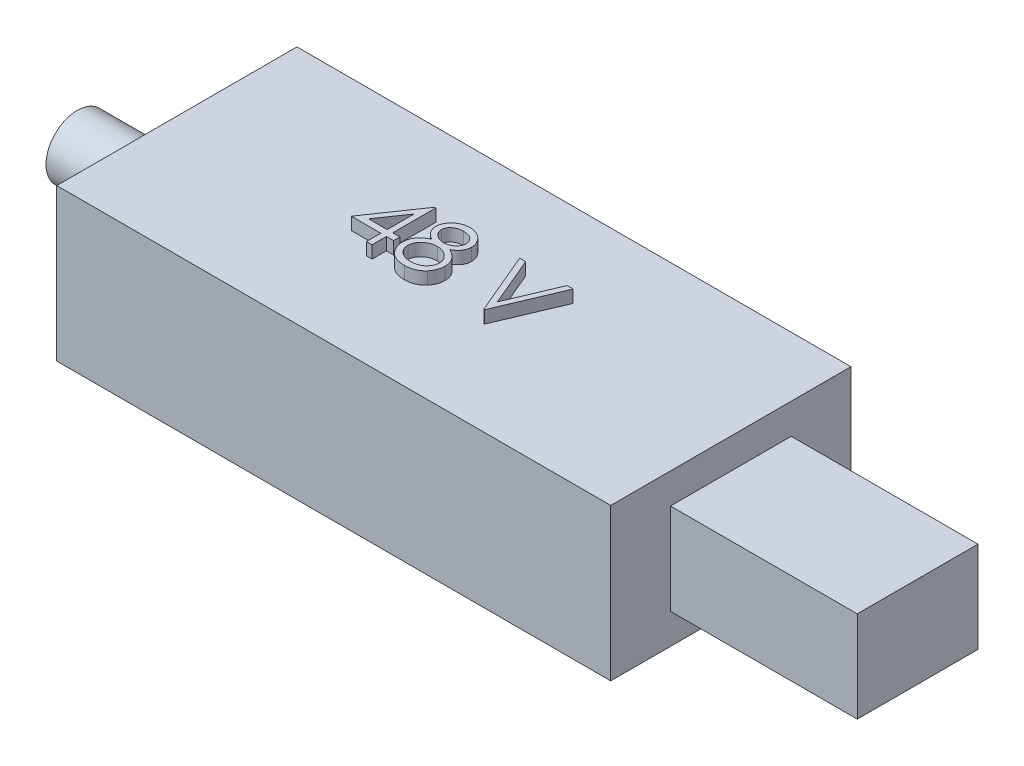
SolidWorks part; units mm, degrees
ref_plane "Front Plane" through (0, 0, 0) normal (0, 0, 1) x (1, 0, 0)
ref_plane "Top Plane" through (0, 0, 0) normal (0, 1, 0) x (1, 0, 0)
ref_plane "Right Plane" through (0, 0, 0) normal (1, 0, 0) x (0, 0, -1)
sketch "Sketch1" plane through (0, 0, 0) normal (0, 1, 0) x (1, 0, 0)
  line L1 (-56.5, 24.5) -> (56.5, 24.5)
  line L2 (-56.5, 24.5) -> (-56.5, -24.5)
  line L3 (-56.5, -24.5) -> (56.5, -24.5)
  line L4 (56.5, 24.5) -> (56.5, -24.5)
  line L5 (-56.5, 24.5) -> (56.5, -24.5) construction
  line L6 (-56.5, -24.5) -> (56.5, 24.5) construction
  point P0 (0, 0)
  dimension "D1" = 113
  dimension "D2" = 49
extrude "Boss-Extrude1" add sketch "Sketch1" along normal blind 31
sketch "Sketch2" plane through (56.5, 0, 0) normal (1, 0, 0) x (0, 0, -1)
  line L0 (-24.5, 15.5) -> (24.5, 15.5) construction
  line L1 (-24.5, 31) -> (-24.5, 0) construction
  line L2 (24.5, 31) -> (24.5, 0) construction
  line L4 (-12.3134, 24.7992) -> (12.3134, 24.7992)
  line L5 (-12.3134, 24.7992) -> (-12.3134, 6.2008)
  line L6 (-12.3134, 6.2008) -> (12.3134, 6.2008)
  line L7 (12.3134, 24.7992) -> (12.3134, 6.2008)
  line L8 (-12.3134, 24.7992) -> (12.3134, 6.2008) construction
  line L9 (-12.3134, 6.2008) -> (12.3134, 24.7992) construction
  point P6 (0, 15.5)
extrude "Boss-Extrude2" add sketch "Sketch2" along normal blind 38.1
sketch "Sketch3" plane through (-56.5, 0, 0) normal (-1, 0, 0) x (0, 0, 1)
  line L0 (-24.5, 15.5) -> (24.5, 15.5) construction
  line L1 (-24.5, 31) -> (-24.5, 0) construction
  line L2 (24.5, 31) -> (24.5, 0) construction
  circle A0 centre (0, 15.5) radius 6.3685
extrude "Boss-Extrude3" add sketch "Sketch3" along normal blind 20.32
sketch "Sketch5" plane through (0, 31, 0) normal (0, 1, 0) x (1, 0, 0)
  text T0 "48 V" font "Century Gothic" height 12.7
extrude "Boss-Extrude4" add sketch "Sketch5" along normal blind 2.54
